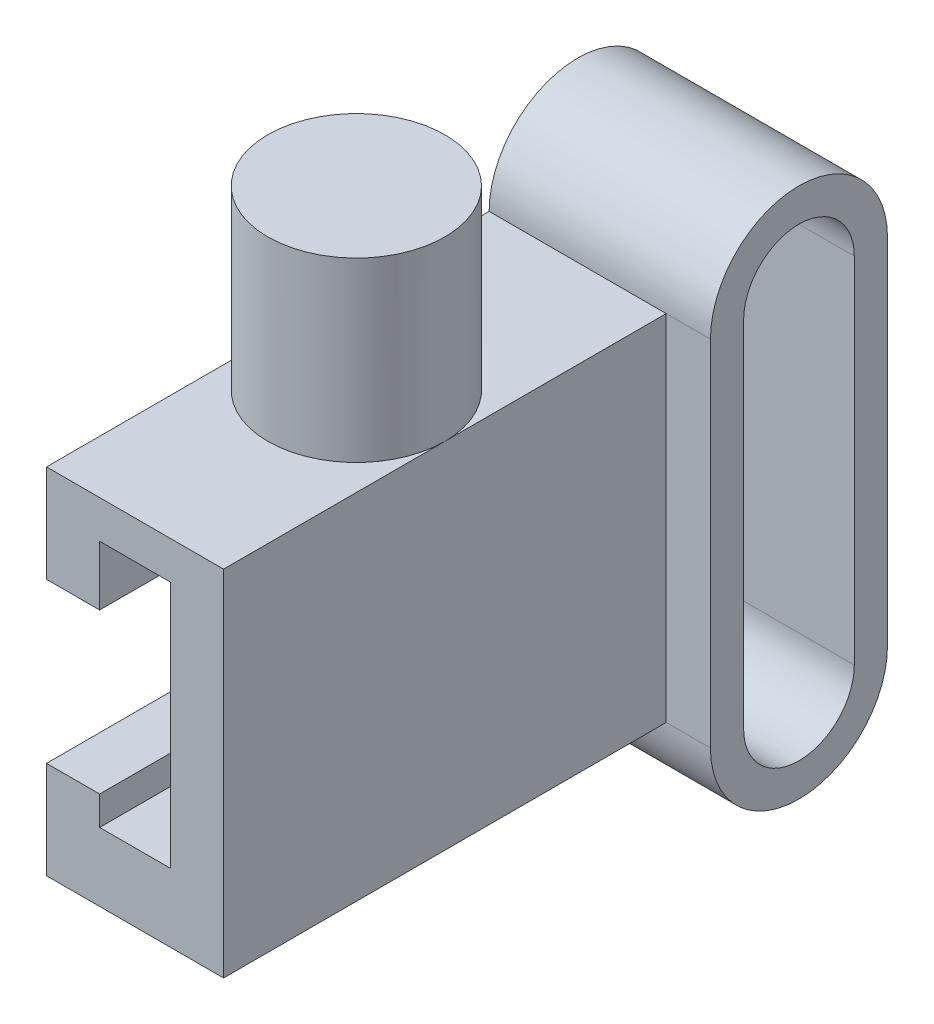
SolidWorks part; units mm, degrees
ref_plane "Front Plane" through (0, 0, 0) normal (0, 0, 1) x (1, 0, 0)
ref_plane "Top Plane" through (0, 0, 0) normal (0, 1, 0) x (1, 0, 0)
ref_plane "Right Plane" through (0, 0, 0) normal (1, 0, 0) x (0, 0, -1)
sketch "Sketch2" plane through (0, 0, 0) normal (1, 0, 0) x (0, 0, -1)
  line L0 (-20, 40) -> (-20, -40)
  line L2 (-12.5, 40) -> (-12.5, -40)
  line L4 (12.5, 40) -> (12.5, -40)
  line L5 (-12.5, 40) -> (12.5, -40) construction
  line L6 (-12.5, -40) -> (12.5, 40) construction
  line L7 (20, 40) -> (20, -40)
  arc A0 (-12.5, 40) -> (12.5, 40) centre (0, 40) cw
  arc A1 (-12.5, -40) -> (12.5, -40) centre (0, -40) ccw
  arc A2 (-20, -40) -> (20, -40) centre (0, -40) ccw
  arc A3 (-20, 40) -> (20, 40) centre (0, 40) cw
  point P0 (0, 0)
  dimension "D1" = 80
  dimension "D2" = 25
  dimension "D3" = 7.5
extrude "Boss-Extrude1" add sketch "Sketch2" against normal blind 50
sketch "Sketch3" plane through (0, 0, 20) normal (0, 0, 1) x (1, 0, 0)
  line L0 (-50, 40) -> (-10, 40)
  line L1 (-50, 40) -> (0, 40) construction
  line L2 (-10, 40) -> (-10, -40)
  line L3 (-50, -40) -> (0, -40) construction
  line L4 (-10, -40) -> (-50, -40)
  line L5 (-50, -40) -> (-50, -18)
  line L6 (-50, 40) -> (-50, -40) construction
  line L7 (-50, -18) -> (-38, -18)
  line L8 (-38, -18) -> (-38, -24.5423)
  line L9 (-38, -24.5423) -> (-22, -24.5423)
  line L10 (-22, -24.5423) -> (-22, 31.4577)
  line L11 (-22, 31.4577) -> (-38, 31.4577)
  line L12 (-38, 31.4577) -> (-38, 18)
  line L13 (-38, 18) -> (-50, 18)
  line L14 (-50, 18) -> (-50, 40)
  dimension "D1" = 22
  dimension "D2" = 12
  dimension "D3" = 56
  dimension "D4" = 16
  dimension "D5" = 40
extrude "Boss-Extrude2" add sketch "Sketch3" along normal blind 100
sketch "Sketch4" plane through (0, 40, 0) normal (0, 1, 0) x (1, 0, 0)
  line L0 (-10, -120) -> (-10, -20) construction
  line L1 (-10, -120) -> (-50, -120) construction
  circle A0 centre (-30, -70) radius 20
  dimension "D1" = 40
  dimension "D2" = 50
extrude "Boss-Extrude3" add sketch "Sketch4" along normal blind 40
